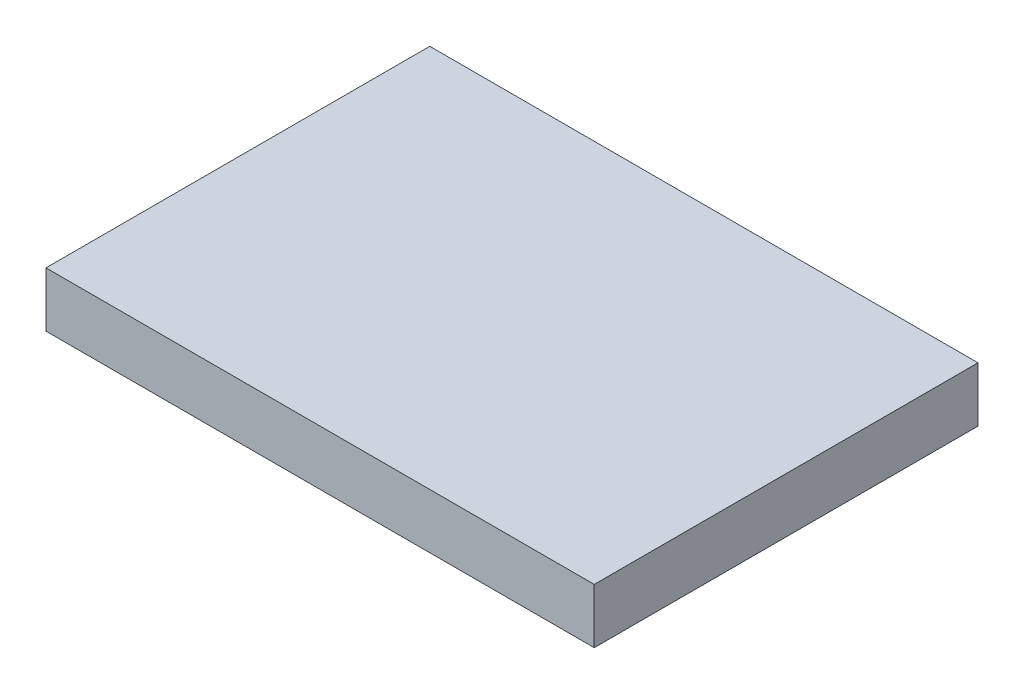
SolidWorks part; units mm, degrees
ref_plane "Front Plane" through (0, 0, 0) normal (0, 0, 1) x (1, 0, 0)
ref_plane "Top Plane" through (0, 0, 0) normal (0, 1, 0) x (1, 0, 0)
ref_plane "Right Plane" through (0, 0, 0) normal (1, 0, 0) x (0, 0, -1)
sketch "Sketch1" plane through (0, 0, 0) normal (0, 1, 0) x (1, 0, 0)
  line L1 (-100, -70) -> (100, -70)
  line L2 (-100, -70) -> (-100, 70)
  line L3 (-100, 70) -> (100, 70)
  line L4 (100, -70) -> (100, 70)
  line L5 (-100, -70) -> (100, 70) construction
  line L6 (-100, 70) -> (100, -70) construction
  point P0 (0, 0)
  dimension "D1" = 140
  dimension "D2" = 200
extrude "Boss-Extrude1" add sketch "Sketch1" along normal blind 20
